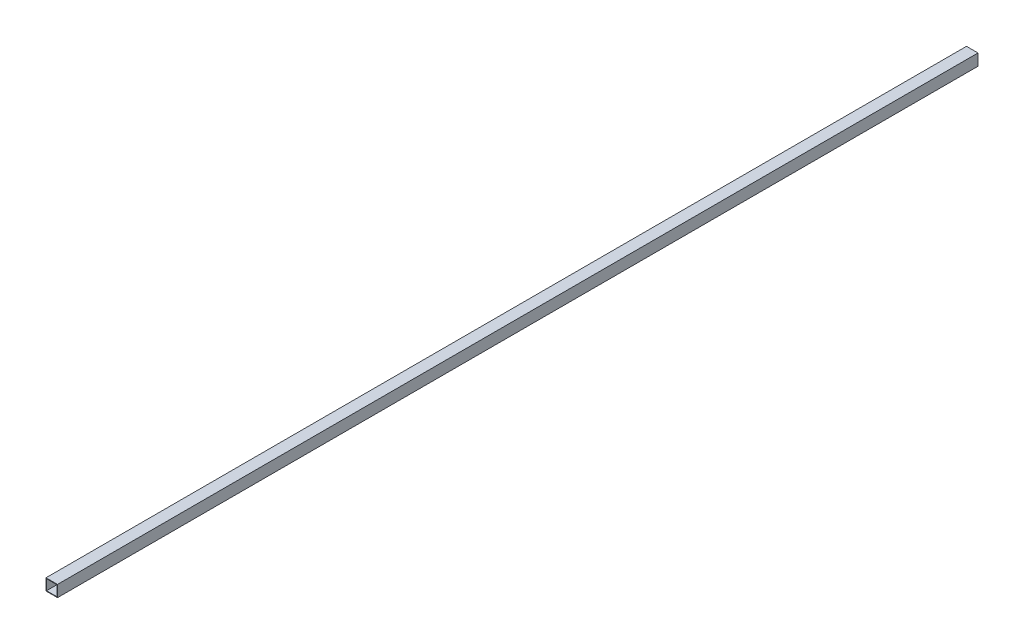
SolidWorks part; units mm, degrees
material "1100-H26 棒材(SS)"
ref_plane "前视基准面" through (0, 0, 0) normal (0, 0, 1) x (1, 0, 0)
ref_plane "上视基准面" through (0, 0, 0) normal (0, 1, 0) x (1, 0, 0)
ref_plane "右视基准面" through (0, 0, 0) normal (1, 0, 0) x (0, 0, -1)
other "Configuration Table"
sketch "草图1" plane through (0, 0, 0) normal (0, 0, 1) x (1, 0, 0)
  line L1 (0, 0) -> (20, 0)
  line L2 (0, 0) -> (0, 20)
  line L3 (0, 20) -> (20, 20)
  line L4 (20, 0) -> (20, 20)
  line L5 (1, 1) -> (19, 1)
  line L6 (1, 1) -> (1, 19)
  line L7 (1, 19) -> (19, 19)
  line L8 (19, 1) -> (19, 19)
  dimension "D1" = 20
  dimension "D2" = 20
  dimension "D3" = 1
  dimension "D4" = 1
  dimension "D5" = 1
  dimension "D6" = 1
extrude "凸台-拉伸1" add sketch "草图1" along normal blind 1600
